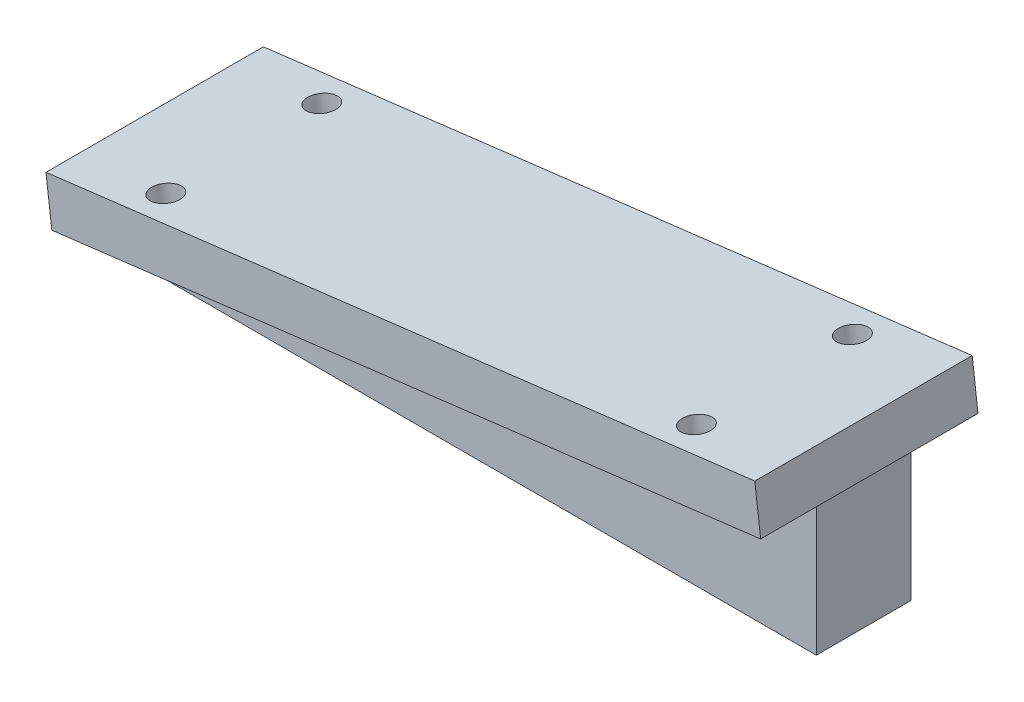
SolidWorks part; units mm, degrees
ref_plane "Front Plane" through (0, 0, 0) normal (0, 0, 1) x (1, 0, 0)
ref_plane "Top Plane" through (0, 0, 0) normal (0, 1, 0) x (1, 0, 0)
ref_plane "Right Plane" through (0, 0, 0) normal (1, 0, 0) x (0, 0, -1)
sketch "Sketch1" plane through (0, 0, 0) normal (0, 1, 0) x (1, 0, 0)
  line L1 (-75, -10) -> (75, -10)
  line L2 (-75, -10) -> (-75, 10)
  line L3 (-75, 10) -> (75, 10)
  line L4 (75, -10) -> (75, 10)
  line L5 (-75, -10) -> (75, 10) construction
  line L6 (-75, 10) -> (75, -10) construction
  point P0 (0, 0)
  dimension "D1" = 20
  dimension "D2" = 150
extrude "Boss-Extrude1" add sketch "Sketch1" along normal mid plane 20
sketch "Sketch2" plane through (0, 0, 0) normal (0, 0, 1) x (1, 0, 0)
  line L0 (-75, 10) -> (75, 10)
  line L1 (75, 10) -> (75, 28.4177)
  line L2 (75, 28.4177) -> (-75, 10)
  dimension "D1" = 7
extrude "Boss-Extrude2" add sketch "Sketch2" along normal mid plane 20
sketch "Sketch3" plane through (0, 0, 0) normal (0, 0, 1) x (1, 0, 0)
  line L6 (75, 28.4177) -> (-75, 10)
  line L7 (75, 28.4177) -> (76.2278, 18.4177)
  line L8 (-75, 10) -> (-73.7722, 0)
  line L9 (76.2278, 18.4177) -> (-73.7722, 0)
  dimension "D1" = 10
extrude "Boss-Extrude3" add sketch "Sketch3" along normal mid plane 46
sketch "Sketch6" plane through (-2.3235, 18.9235, 0) normal (-0.1219, 0.9925, 0) x (0.9925, 0.1219, 0)
  line L0 (-54.2223, -16.5) -> (-54.2223, 16.5) construction
  line L1 (-54.2223, 16.5) -> (58.9042, 16.5) construction
  line L2 (58.9042, 16.5) -> (58.9042, -16.5) construction
  line L3 (58.9042, -16.5) -> (-54.2223, -16.5) construction
  line L4 (77.9042, 23) -> (-73.2223, 23) construction
  line L5 (77.9042, -23) -> (-73.2223, -23) construction
  line L6 (-73.2223, 10) -> (-73.2223, -10) construction
  line L7 (77.9042, -23) -> (77.9042, 23) construction
  circle A0 centre (-54.2223, 16.5) radius 3
  circle A1 centre (58.9042, 16.5) radius 3
  circle A2 centre (58.9042, -16.5) radius 3
  circle A3 centre (-54.2223, -16.5) radius 3
  dimension "D1" = 6
  dimension "D2" = 6.5
  dimension "D3" = 6.5
  dimension "D4" = 19
  dimension "D5" = 19
extrude "Cut-Extrude2" cut sketch "Sketch6" against normal blind 46
